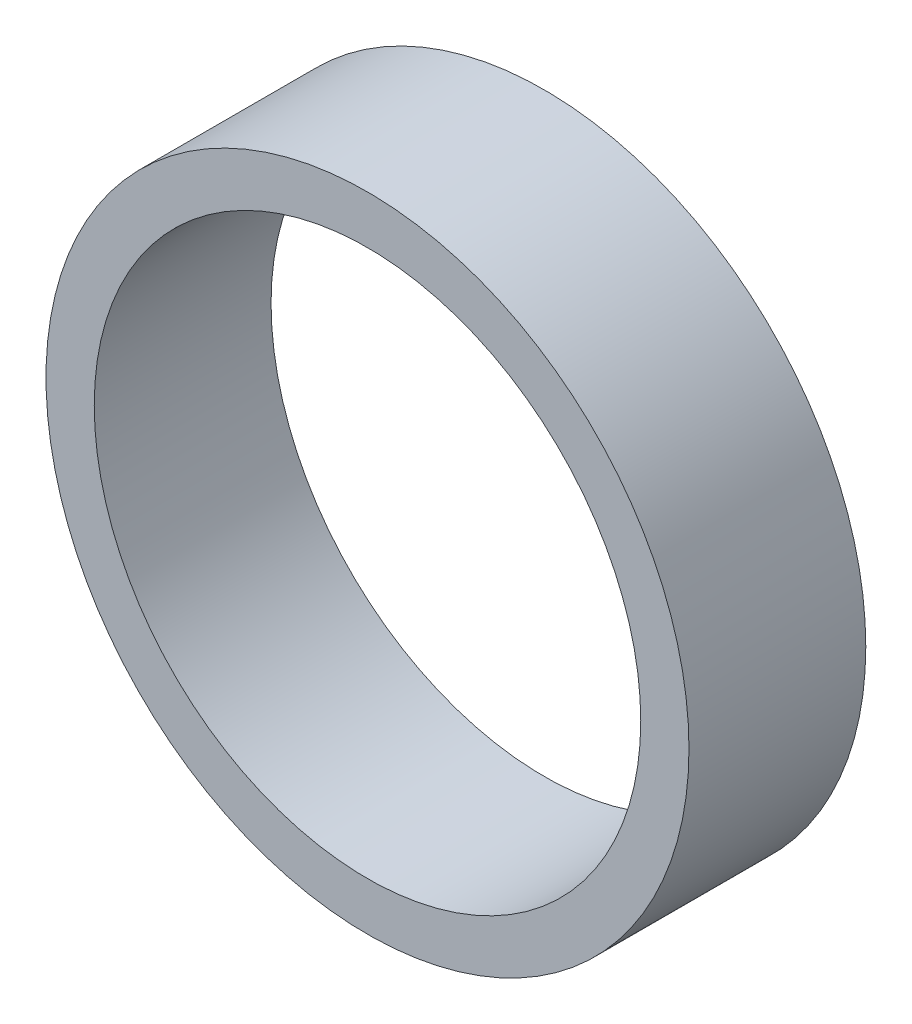
SolidWorks part; units mm, degrees
ref_plane "前视基准面" through (0, 0, 0) normal (0, 0, 1) x (1, 0, 0)
ref_plane "上视基准面" through (0, 0, 0) normal (0, 1, 0) x (1, 0, 0)
ref_plane "右视基准面" through (0, 0, 0) normal (1, 0, 0) x (0, 0, -1)
sketch "草图1" plane through (0, 0, 0) normal (0, 0, 1) x (1, 0, 0)
  circle A0 centre (0, 0) radius 40
  circle A1 centre (0, 0) radius 34
  dimension "D1" = 80
  dimension "D2" = 68
extrude "凸台-拉伸1" add sketch "草图1" along normal blind 22
